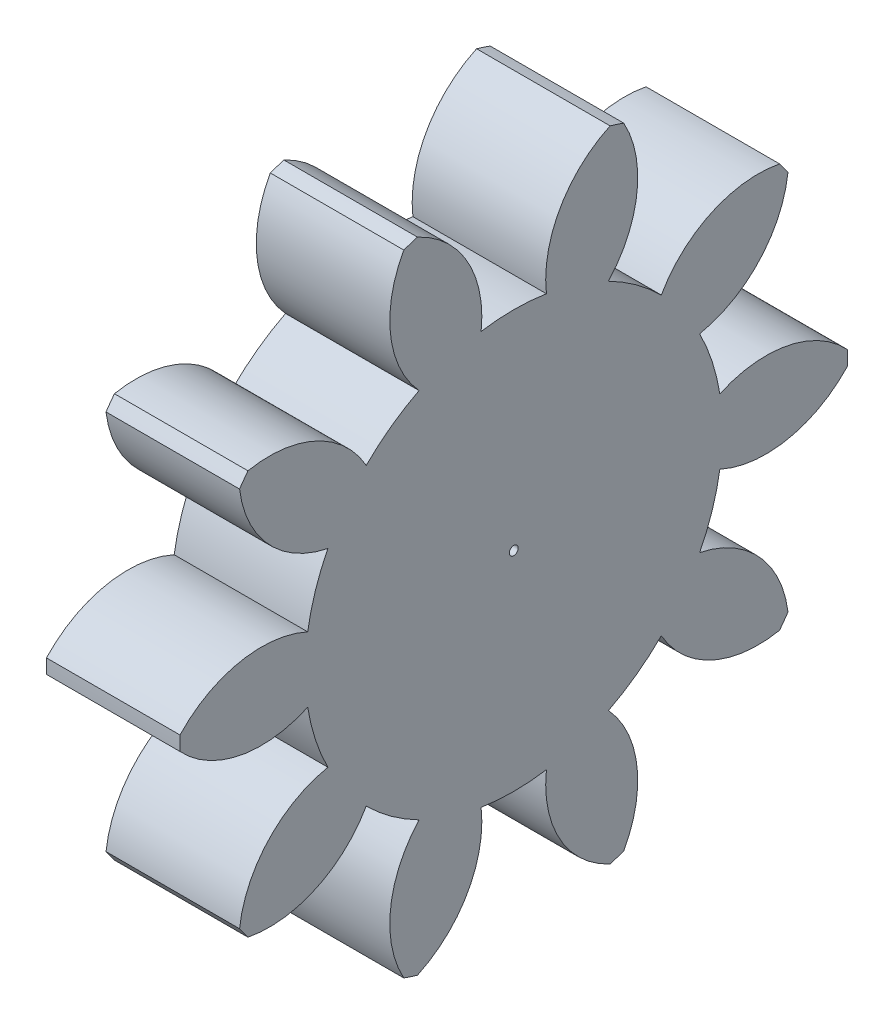
SolidWorks part; units mm, degrees
ref_plane "Plane1" through (0, 0, 0) normal (0, 0, 1) x (1, 0, 0)
ref_plane "Plane2" through (0, 0, 0) normal (0, 1, 0) x (1, 0, 0)
ref_plane "Plane3" through (0, 0, 0) normal (1, 0, 0) x (0, 0, -1)
other "Configuration Table"
sketch "HoldingSke" plane through (0, 0, 0) normal (0, 1, 0) x (1, 0, 0)
  line L0 (0, 0) -> (0.197, -0.0347)
  line L1 (-15, 0) -> (100, 0) construction
  line L2 (0, 0) -> (-2.1039, 2.3779)
  line L3 (0, 0) -> (-11.863, 4.5341)
  line L4 (0, 0) -> (8.5048, 1.4996)
  line L5 (0, 0) -> (-46.8476, -17.4728)
  line L6 (0, 0) -> (-9.9476, -6.7116)
  line L7 (-2.1039, 2.3779) -> (8.6586, 51.2059)
  line L8 (-76.2, 54.61) -> (-76.1, 54.61)
  line L9 (-71.009, 38.7566) -> (-53.1078, 45.2721)
  line L10 (-76.2, 71.12) -> (104.1128, 71.12)
  line L11 (0, 0) -> (-12, 0)
  line L12 (-76.2, 101.6) -> (-76.033, 101.6)
  line L13 (24.9733, 27.94) -> (52.9518, 28.4284)
  line L14 (24.9733, 27.94) -> (24.9743, 27.94)
  line L15 (24.9733, 27.94) -> (100.4006, 29.5858)
  line L16 (-63.627, -5) -> (-12.827, -5)
  circle A0 centre (0, 0) radius 0.4
  circle A1 centre (0, 0) radius 18.749
  circle A2 centre (0, 0) radius 37.5
  circle A3 centre (0, 0) radius 0.4
  dimension "MHD" = 37.498
  dimension "Hub_dia" = 75
  dimension "Bore" = 0.8
  dimension "MBD" = 0.8
  dimension "Num_teeth" = 10
  dimension "Pitch" = 0.2
  dimension "Overall_len" = 50
  dimension "Show_teeth" = 10
  dimension "Thickness" = 12
  dimension "OAL" = 50.0001
  dimension "T_dim" = 0.1
  dimension "Ap" = 20
  dimension "H" = 19.05
  dimension "Pitch_radius" = 180.3128
  dimension "Width" = 12
  dimension "Backlash" = 0.167
  dimension "Addendum_fac" = 1
  dimension "Dedendum_fac" = 1.25
  dimension "Clearance_fac" = 0.25
  dimension "Dedendum_add" = 0.001
  dimension "Module" = 5
sketch "BasProSke" plane through (0, 0, 0) normal (0, 1, 0) x (1, 0, 0)
  line L0 (-10, 0) -> (60, 0) construction
  line L1 (0, 0) -> (0, 30)
  line L2 (0, 0) -> (12, 0)
  line L3 (12, 0) -> (12, 30)
  line L4 (12, 30) -> (0, 30)
  dimension "Thickness" = 12
  dimension "Diameter" = 60
revolve "Base-Revolve" add sketch "BasProSke" angle 360 about L0
sketch "TooCutSke" plane through (0, 0, 0) normal (1, 0, 0) x (0, 0, -1)
  line L1 (0, 0) -> (0, 107) construction
  line L2 (0, 0) -> (-4.2026, 24.6442) construction
  line L3 (0, 0) -> (-15.2881, 47.0521) construction
  line L4 (-4.2026, 24.6442) -> (-7.6441, 23.526) construction
  arc A0 (2.9333, 18.5181) -> (-2.9333, 18.5181) centre (0, 0) ccw
  arc A1 (8.6913, 28.74) -> (-8.6913, 28.74) centre (0, 0) ccw
  circle A2 centre (0, 0) radius 25 construction
  circle A3 centre (0, 0) radius 23.4923 construction
  arc A4 (-2.9333, 18.5181) -> (-8.6913, 28.74) centre (-12.8686, 19.6542) ccw
  arc A5 (8.6913, 28.74) -> (2.9333, 18.5181) centre (12.8686, 19.6542) ccw
  dimension "Root_dia" = 37.498
  dimension "Overcut_dia" = 60.0508
  dimension "Pitch_dia" = 50
  dimension "Base_dia" = 46.9846
  dimension "Flank_rad" = 10
  dimension "Half_ang" = 18
  dimension "Half_CT" = 3.6186
extrude "ToothCut" cut sketch "TooCutSke" along normal through all
fillet "Breaks" [suppressed] radius 0.1
fillet "RootFillets" [suppressed] radius 1.251
pattern_circular "TeethCuts" count 10 every 36 about axis through (-10, 0, 0) along (1, 0, 0) of "ToothCut", "RootFillets", "Breaks"
sketch "HubNeaOneSke" plane through (0, 0, 0) normal (-1, 0, 0) x (0, 0, 1)
  circle A0 centre (0, 0) radius 18.749
  dimension "Diameter" = 37.498
extrude "HubNearOne" [suppressed] add sketch "HubNeaOneSke" along normal blind 38.0001
sketch "HubNeaBotSke" plane through (0, 0, 0) normal (-1, 0, 0) x (0, 0, 1)
  circle A0 centre (0, 0) radius 18.749
  dimension "Diameter" = 37.498
extrude "HubNearBoth" [suppressed] add sketch "HubNeaBotSke" along normal blind 19
ref_plane "FarPln" through (12, 0, 0) normal (1, 0, 0) x (0, 0, -1)
sketch "HubFarSke" plane through (12, 0, 0) normal (1, 0, 0) x (0, 0, -1)
  circle A0 centre (0, 0) radius 18.749
  dimension "Diameter" = 37.498
extrude "HubFar" [suppressed] add sketch "HubFarSke" along normal blind 19
sketch "BorSke" plane through (0, 0, 0) normal (1, 0, 0) x (0, 0, -1)
  circle A0 centre (0, 0) radius 0.4
  dimension "Diameter" = 0.8
extrude "Bore" cut sketch "BorSke" along normal mid plane 100.0001
sketch "KeySke" plane through (0, 0, 0) normal (1, 0, 0) x (0, 0, -1)
  line L0 (-0.05, 0) -> (-0.05, 0.5)
  line L1 (-0.05, 0.5) -> (0.05, 0.5)
  line L2 (0.05, 0.5) -> (0.05, 0)
  line L3 (0, 0) -> (0, 34) construction
  line L4 (-0.05, 0) -> (0.05, 0)
  dimension "Offset" = 0.5
  dimension "Width" = 0.1
extrude "Keyway" [suppressed] cut sketch "KeySke" along normal mid plane 100.0001
pattern_circular "Keyway2" [suppressed] count 2 every 90 about axis through (-10, 0, 0) along (1, 0, 0)
equation "' \"Module@HoldingSke\" = 6.35"
equation "' \"Num_teeth@HoldingSke\" = 12"
equation "' \"Ap@HoldingSke\" =  20"
equation "' \"Ap@HoldingSke\" = 20"
equation "' \"Width@HoldingSke\" = 0.5 * 25.4"
equation "' \"Hub_dia@HoldingSke\"= 1 * 25.4"
equation "' \"Hub_dia@HoldingSke\" = 1 * 25.4"
equation "' \"Overall_len@HoldingSke\" = 1.0 * 25.4"
equation "' \"Bore@HoldingSke\" = 0.75 * 25.4"
equation "' \"T_dim@HoldingSke\" = 0.1 * 25.4"
equation "' \"Width@KeySke\" = 0.25 * 25.4"
equation "' \"Show_teeth@HoldingSke\" = 13"
equation "' \"Backlash@HoldingSke\" = 0.009 * 25.4"
equation "' \"Addendum_fac@HoldingSke\" = 1.0"
equation "' \"Dedendum_fac@HoldingSke\" = 1.25"
equation "' \"Dedendum_add@HoldingSke\" = 0.00005 * 25.4"
equation "' \"Clearance_fac@HoldingSke\" = 0.25"
equation "\"Pitch@HoldingSke\" = 1 / \"Module@HoldingSke\""
equation "\"Overcut_dia@TooCutSke\" = (\"Num_teeth@HoldingSke\" + 2 * \"Addendum_fac@HoldingSke\") / \"Pitch@HoldingSke\" + 0.002 * 25.4"
equation "\"Pitch_dia@TooCutSke\" = \"Num_teeth@HoldingSke\" / \"Pitch@HoldingSke\""
equation "\"Base_dia@TooCutSke\" = \"Num_teeth@HoldingSke\" / \"Pitch@HoldingSke\" * cos((\"Ap@HoldingSke\"  * 3.14159265 / 180))"
equation "\"Root_dia@TooCutSke\" = (\"Num_teeth@HoldingSke\" + 2) / \"Pitch@HoldingSke\" - 2 * (\"Addendum_fac@HoldingSke\" + \"Dedendum_fac@HoldingSke\") / \"Pitch@HoldingSke\" - \"Dedendum_add@HoldingSke\" * 2"
equation "\"Half_ang@TooCutSke\" = 180 / \"Num_teeth@HoldingSke\""
equation "\"Half_CT@TooCutSke\" = \"Num_teeth@HoldingSke\" / \"Pitch@HoldingSke\" * sin((3.14159265 / 2 / \"Num_teeth@HoldingSke\")) / 2 - 7 * \"Backlash@HoldingSke\" / 4"
equation "\"Flank_rad@TooCutSke\" = \"Num_teeth@HoldingSke\" / \"Pitch@HoldingSke\" / 5"
equation "\"Radius@RootFillets\" = \"Clearance_fac@HoldingSke\" / \"Pitch@HoldingSke\" + \"Dedendum_add@HoldingSke\""
equation "\"Break_rad@Breaks\" = 0.02 / \"Pitch@HoldingSke\""
equation "\"Thickness@HoldingSke\" = \"Width@HoldingSke\""
equation "\"OAL@HoldingSke\" = \"Thickness@HoldingSke\""
equation "\"MHD@HoldingSke\" = (\"Num_teeth@HoldingSke\" + 2) / \"Pitch@HoldingSke\" - 2 * (\"Addendum_fac@HoldingSke\" + \"Dedendum_fac@HoldingSke\")  / \"Pitch@HoldingSke\" - \"Dedendum_add@HoldingSke\" * 2"
equation "\"MBD@HoldingSke\" = (\"Num_teeth@HoldingSke\" + 2) / \"Pitch@HoldingSke\" - 2 * (\"Addendum_fac@HoldingSke\" + \"Dedendum_fac@HoldingSke\")  / \"Pitch@HoldingSke\" - \"Dedendum_add@HoldingSke\" * 2 - 0.002 * 25.4"
equation "\"MHD@HoldingSke\" = ((sgn( \"MHD@HoldingSke\" - \"Hub_dia@HoldingSke\" )-1)*( \"MHD@HoldingSke\" - \"Hub_dia@HoldingSke\" ))/-2+ \"Hub_dia@HoldingSke\""
equation "\"MBD@HoldingSke\" = ((sgn( \"MBD@HoldingSke\" - \"Bore@HoldingSke\" )-1)*( \"MBD@HoldingSke\" - \"Bore@HoldingSke\" ))/-2+ \"Bore@HoldingSke\""
equation "\"OAL@HoldingSke\" = ((sgn( \"OAL@HoldingSke\" - \"Overall_len@HoldingSke\" )+1)*( \"OAL@HoldingSke\" - \"Overall_len@HoldingSke\" ))/2 + \"Overall_len@HoldingSke\" + 0.000002 * 25.4"
equation "\"Num_teeth@TeethCuts\" = int( \"Show_teeth@HoldingSke\" ) + 1"
equation "\"Num_teeth@TeethCuts\" = ((sgn( \"Num_teeth@TeethCuts\" - \"Num_teeth@HoldingSke\" )-1)*( \"Num_teeth@TeethCuts\" - \"Num_teeth@HoldingSke\" ))/-2+ \"Num_teeth@HoldingSke\""
equation "\"Num_teeth@TeethCuts\" = ((sgn( \"Num_teeth@TeethCuts\" - 2.0)+1)*( \"Num_teeth@TeethCuts\" - 2.0))/2 +2.0"
equation "\"Angle@TeethCuts\" = 360.0 / \"Num_teeth@HoldingSke\""
equation "\"Diameter@BasProSke\" = (\"Num_teeth@HoldingSke\" + 2 * \"Addendum_fac@HoldingSke\") / \"Pitch@HoldingSke\""
equation "\"Thickness@BasProSke\"  = \"Thickness@HoldingSke\""
equation "' \"Fillet_rad@BasProSke\" =  \"Thickness@HoldingSke\" * 0.05"
equation "' \"Fillet_rad@BasProSke\" = \"Thickness@HoldingSke\" * 0.05"
equation "\"MHD@HoldingSke\" = ((sgn( \"MHD@HoldingSke\" - \"Root_dia@TooCutSke\" )-1)*( \"MHD@HoldingSke\" - \"Root_dia@TooCutSke\" ))/-2+ \"Root_dia@TooCutSke\""
equation "\"Diameter@HubNeaOneSke\" = \"MHD@HoldingSke\""
equation "\"Length@HubNearOne\" = \"OAL@HoldingSke\" - \"Thickness@BasProSke\""
equation "\"Diameter@HubNeaBotSke\" = \"MHD@HoldingSke\""
equation "\"Length@HubNearBoth\" = ( \"OAL@HoldingSke\" - \"Thickness@BasProSke\" ) / 2.0"
equation "\"Thickness@FarPln\" = \"Thickness@BasProSke\""
equation "\"Diameter@HubFarSke\" = \"MHD@HoldingSke\""
equation "\"Length@HubFar\" = ( \"OAL@HoldingSke\" - \"Thickness@BasProSke\" ) / 2.0"
equation "\"Diameter@BorSke\" = \"MBD@HoldingSke\""
equation "\"D1@Bore\" = \"OAL@HoldingSke\" * 2.0"
equation "\"D1@Keyway\" = \"OAL@HoldingSke\" * 2.0"
equation "\"Offset@KeySke\" = \"T_dim@HoldingSke\" + \"MBD@HoldingSke\" / 2.0"
